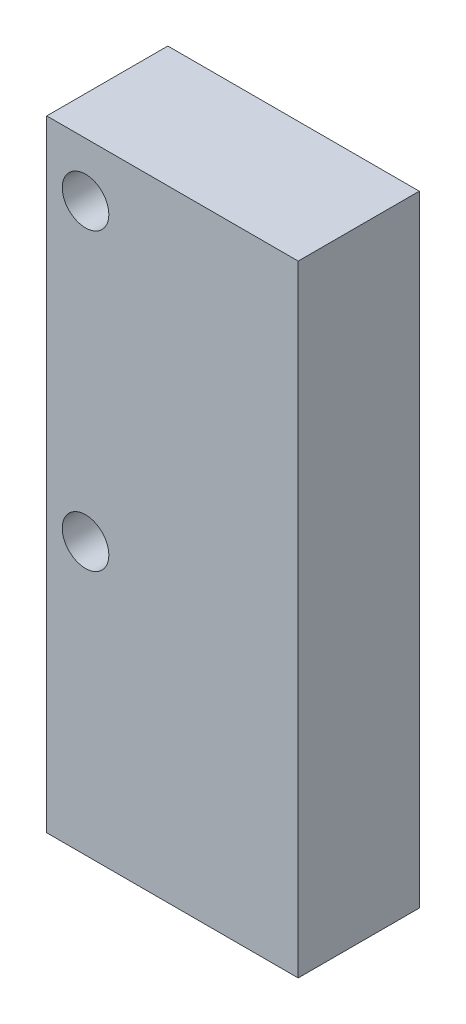
SolidWorks part; units mm, degrees
ref_plane "Front Plane" through (0, 0, 0) normal (0, 0, 1) x (1, 0, 0)
ref_plane "Top Plane" through (0, 0, 0) normal (0, 1, 0) x (1, 0, 0)
ref_plane "Right Plane" through (0, 0, 0) normal (1, 0, 0) x (0, 0, -1)
sketch "Sketch1" plane through (0, 0, 0) normal (0, 0, 1) x (1, 0, 0)
  line L1 (-8.1, 20) -> (8.1, 20)
  line L2 (-8.1, 20) -> (-8.1, -20)
  line L3 (-8.1, -20) -> (8.1, -20)
  line L4 (8.1, 20) -> (8.1, -20)
  line L5 (-8.1, 20) -> (8.1, -20) construction
  line L6 (-8.1, -20) -> (8.1, 20) construction
  point P0 (0, 0)
  dimension "D1" = 16.2
  dimension "D2" = 40
extrude "Boss-Extrude1" add sketch "Sketch1" along normal blind 7.8
sketch "Sketch2" plane through (0, 0, 7.8) normal (0, 0, 1) x (1, 0, 0)
  line L0 (-5.6, 20) -> (-5.6, -20) construction
  line L1 (8.1, 20) -> (-8.1, 20) construction
  line L2 (-8.1, -20) -> (8.1, -20) construction
  line L3 (-8.1, 20) -> (-8.1, -20) construction
  circle A0 centre (-5.6, 16.5) radius 1.5
  circle A1 centre (-5.6, -2.5) radius 1.5
  dimension "D1" = 3
  dimension "D2" = 3
  dimension "D3" = 19
  dimension "D4" = 3.5
  dimension "D5" = 2.5
extrude "Cut-Extrude1" cut sketch "Sketch2" against normal through all
